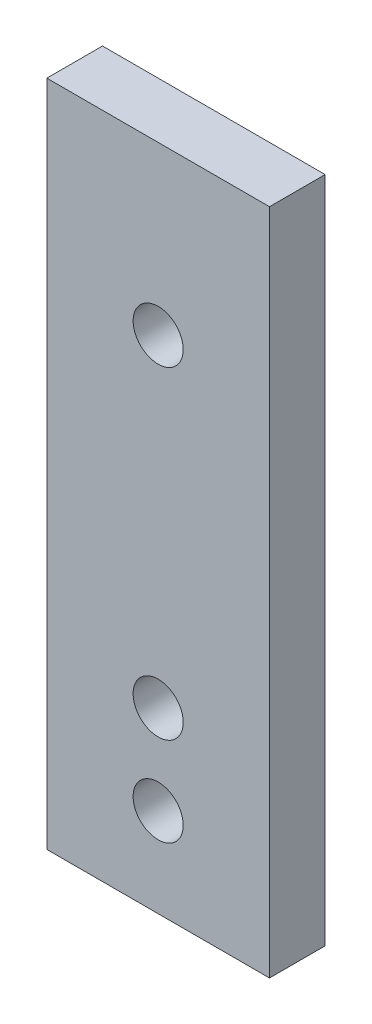
SolidWorks part; units mm, degrees
ref_plane "Front Plane" through (0, 0, 0) normal (0, 0, 1) x (1, 0, 0)
ref_plane "Top Plane" through (0, 0, 0) normal (0, 1, 0) x (1, 0, 0)
ref_plane "Right Plane" through (0, 0, 0) normal (1, 0, 0) x (0, 0, -1)
sketch "Sketch1" plane through (0, 0, 0) normal (0, 0, 1) x (1, 0, 0)
  line L0 (10, 60) -> (10, 0) construction
  line L1 (0, 0) -> (20, 0)
  line L2 (0, 0) -> (0, 60)
  line L3 (0, 60) -> (20, 60)
  line L4 (20, 0) -> (20, 60)
  line L5 (0, 45) -> (20, 45) construction
  line L6 (0, 8) -> (20, 8) construction
  line L7 (0, 16) -> (20, 16) construction
  circle A0 centre (10, 45) radius 2.25
  circle A1 centre (10, 16) radius 2.25
  circle A2 centre (10, 8) radius 2.25
  dimension "D4" = 4.5
  dimension "D1" = 20
  dimension "D2" = 60
  dimension "D3" = 15
  dimension "D5" = 8
  dimension "D6" = 8
extrude "Boss-Extrude1" add sketch "Sketch1" along normal blind 5
